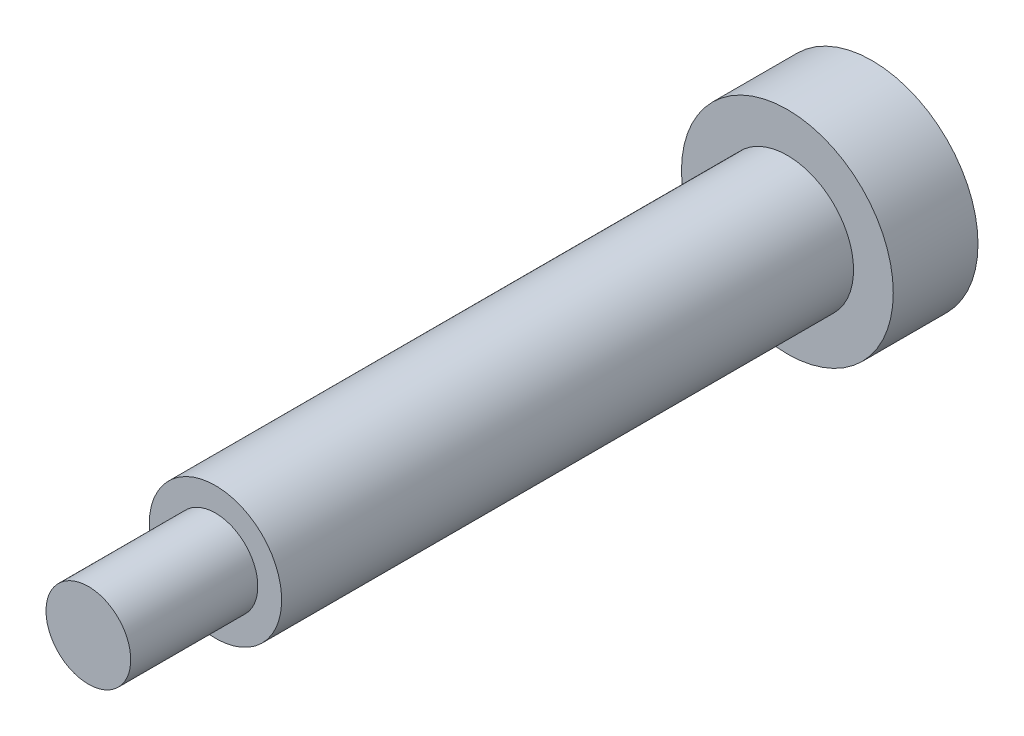
SolidWorks part; units mm, degrees
ref_plane "Front Plane" through (0, 0, 0) normal (0, 0, 1) x (1, 0, 0)
ref_plane "Top Plane" through (0, 0, 0) normal (0, 1, 0) x (1, 0, 0)
ref_plane "Right Plane" through (0, 0, 0) normal (1, 0, 0) x (0, 0, -1)
sketch "Sketch1" plane through (0, 0, 0) normal (0, 1, 0) x (1, 0, 0)
  line L0 (0, 34.6364) -> (0, -33.2727) construction
  line L1 (0, 0) -> (2, 0)
  line L2 (2, 0) -> (2, 6)
  line L3 (2, 6) -> (3.125, 6)
  line L4 (3.125, 6) -> (3.125, 33)
  line L5 (3.125, 33) -> (5, 33)
  line L6 (5, 33) -> (5, 37)
  line L7 (5, 37) -> (0, 37)
  line L8 (0, 37) -> (0, 0)
  dimension "D1" = 4
  dimension "D2" = 5
  dimension "D3" = 6.25
  dimension "D4" = 27
  dimension "D5" = 6
  dimension "D6" = 4
revolve "Revolve1" add sketch "Sketch1" angle 360 about L0
